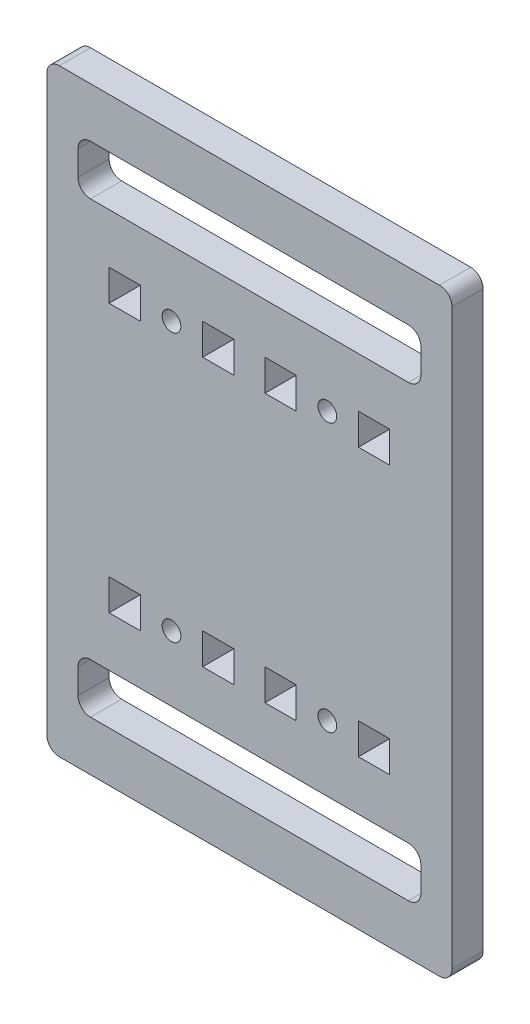
SolidWorks part; units mm, degrees
ref_plane "Plan de face" through (0, 0, 0) normal (0, 0, 1) x (1, 0, 0)
ref_plane "Plan de dessus" through (0, 0, 0) normal (0, 1, 0) x (1, 0, 0)
ref_plane "Plan de droite" through (0, 0, 0) normal (1, 0, 0) x (0, 0, -1)
sketch "Esquisse1" plane through (0, 0, 0) normal (0, 0, 1) x (1, 0, 0)
  line L0 (0, 0) -> (17.8582, 0) construction
  line L1 (-45, 48) -> (20, 48)
  line L2 (20, 48) -> (20, -48)
  line L3 (20, -48) -> (-45, -48)
  line L4 (-45, -48) -> (-45, 48) construction
  line L13 (0, 0) -> (0, 13.4404) construction
  line L16 (-45, -48) -> (-45, 48)
  line L18 (-12.5, -48) -> (-12.5, 48) construction
  line L19 (-40, -40) -> (-40, -32)
  line L20 (-40, 40) -> (15, 40)
  line L21 (-40, 40) -> (-40, 32)
  line L22 (-40, 32) -> (15, 32)
  line L23 (15, 40) -> (15, 32)
  line L24 (-40, -32) -> (15, -32)
  line L25 (15, -40) -> (15, -32)
  line L26 (-40, -40) -> (15, -40)
  point P12 (0, 0)
  line B0 (-5, 24) -> (-10, 24)
  line B1 (-5, 24) -> (-5, 19)
  line B2 (-5, 19) -> (-10, 19)
  line B3 (-10, 24) -> (-10, 19)
  line B4 (5, 24) -> (10, 24)
  line B5 (5, 24) -> (5, 19)
  line B6 (5, 19) -> (10, 19)
  line B7 (10, 24) -> (10, 19)
  line B8 (0, 21.5) -> (0, 27.7802) construction
  circle B9 centre (0, 21.5) radius 1.5
  line B10 (-5, -24) -> (-10, -24)
  line B11 (-5, -24) -> (-5, -19)
  line B12 (-5, -19) -> (-10, -19)
  line B13 (-10, -24) -> (-10, -19)
  line B14 (5, -24) -> (10, -24)
  line B15 (5, -24) -> (5, -19)
  line B16 (5, -19) -> (10, -19)
  line B17 (10, -24) -> (10, -19)
  circle B18 centre (0, -21.5) radius 1.5
  line B19 (-20, 24) -> (-15, 24)
  line B20 (-20, 24) -> (-20, 19)
  line B21 (-20, 19) -> (-15, 19)
  line B22 (-15, 24) -> (-15, 19)
  line B23 (-30, 24) -> (-35, 24)
  line B24 (-30, 24) -> (-30, 19)
  line B25 (-30, 19) -> (-35, 19)
  line B26 (-35, 24) -> (-35, 19)
  circle B27 centre (-25, 21.5) radius 1.5
  line B28 (-20, -24) -> (-15, -24)
  line B29 (-20, -24) -> (-20, -19)
  line B30 (-20, -19) -> (-15, -19)
  line B31 (-15, -24) -> (-15, -19)
  line B32 (-30, -24) -> (-35, -24)
  line B33 (-30, -24) -> (-30, -19)
  line B34 (-30, -19) -> (-35, -19)
  line B35 (-35, -24) -> (-35, -19)
  circle B36 centre (-25, -21.5) radius 1.5
sketch_block_instance "Trou M3 plots 5mm-52"
sketch_block "Trou M3 plots 5mm" parameters "D2"=3, "D1"=5, "D3"=5, "D4"=8
sketch_block_instance "Trou M3 plots 5mm-54"
sketch_block_instance "Trou M3 plots 5mm-55"
sketch_block_instance "Trou M3 plots 5mm-56" parameters "D2"=5.3783, "D9"=8.9498, "D1"=52.3229, "D4"=1.9713, "D5"=1.9713, "D6"=22, "D7"=23.6003, "D8"=48, "D10"=12.4801, "D11"=14.5466, "D12"=21, "D3"=54
extrude "Boss.-Extru.1" add sketch "Esquisse1" along normal blind 5
fillet "Congé1" radius 2 12 edges at (20, -48, 2.5) (-45, -48, 2.5) (20, 48, 2.5) (-40, -40, 2.5) (-40, -32, 2.5) (15, -32, 2.5) (15, -40, 2.5) (15, 32, 2.5) (15, 40, 2.5) (-40, 32, 2.5) (-40, 40, 2.5) (-45, 48, 2.5)
